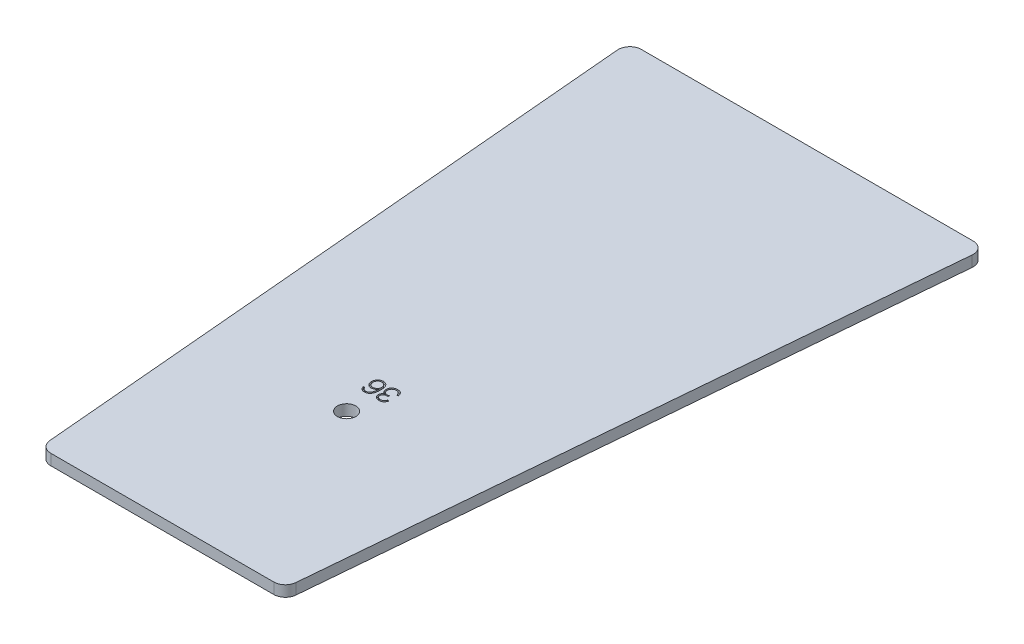
SolidWorks part; units mm, degrees
material "Acrylic (Medium-high impact)"
ref_plane "Front Plane" through (0, 0, 0) normal (0, 0, 1) x (1, 0, 0)
ref_plane "Top Plane" through (0, 0, 0) normal (0, 1, 0) x (1, 0, 0)
ref_plane "Right Plane" through (0, 0, 0) normal (1, 0, 0) x (0, 0, -1)
sketch "Sketch1" plane through (0, 0, 0) normal (0, 1, 0) x (1, 0, 0)
  line L0 (0, 0) -> (0, -355.6) construction
  line L1 (-67.31, 0) -> (67.31, 0)
  line L2 (67.31, 0) -> (98.421, -355.6)
  line L3 (98.421, -355.6) -> (-98.421, -355.6)
  line L4 (-67.31, 0) -> (-98.421, -355.6)
  dimension "D1" = 355.6
  dimension "D2" = 10
  dimension "D3" = 134.62
extrude "Boss-Extrude1" add sketch "Sketch1" along normal blind 5.9944
sketch "Sketch2" plane through (0, 5.9944, 0) normal (0, 1, 0) x (1, 0, 0)
  line L0 (0, 0) -> (0, -101.6) construction
  line L1 (67.31, 0) -> (-67.31, 0) construction
  circle A0 centre (0, -101.6) radius 5.08
  dimension "D1" = 10.16
  dimension "D2" = 101.6
extrude "Cut-Extrude1" cut sketch "Sketch2" against normal through all
sketch "Sketch3" plane through (0, 5.9944, 0) normal (0, 1, 0) x (1, 0, 0)
  line L1 (-7.62, -125.8313) -> (7.62, -125.8313) construction
  line L2 (-7.62, -125.8313) -> (-7.62, -114.3) construction
  line L3 (-7.62, -114.3) -> (7.62, -114.3) construction
  line L4 (7.62, -125.8313) -> (7.62, -114.3) construction
  line L5 (0, -114.3) -> (0, -101.6) construction
  text T0 "36"
  dimension "D1" = 12.7
  dimension "D2" = 15.24
extrude "Cut-Extrude2" cut sketch "Sketch3" against normal blind 1.27
fillet "Fillet1" radius 6.35 4 edges at (-98.421, 2.9972, 355.6) (98.421, 2.9972, 355.6) (-67.31, 2.9972, 0) (67.31, 2.9972, 0)
move or copy body "Body-Move/Copy1" bodies to move or copy 103 copy no rotation origin (0, 0, 177.8) rotation axis (0, 1, 0) rotation angle 180
